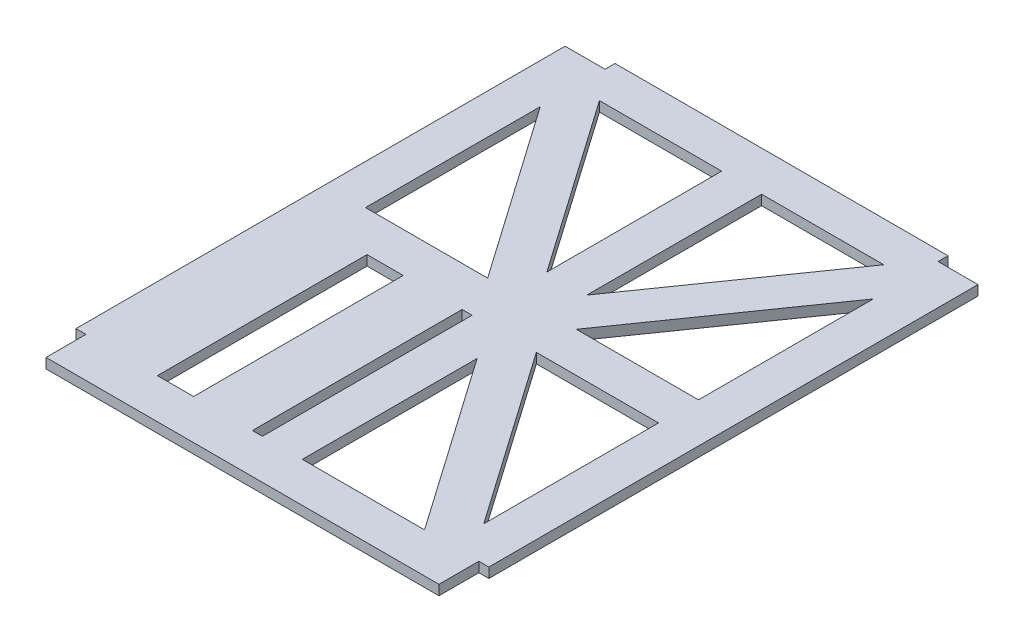
SolidWorks part; units mm, degrees
ref_plane "Front Plane" through (0, 0, 0) normal (0, 0, 1) x (1, 0, 0)
ref_plane "Top Plane" through (0, 0, 0) normal (0, 1, 0) x (1, 0, 0)
ref_plane "Right Plane" through (0, 0, 0) normal (1, 0, 0) x (0, 0, -1)
sketch "Sketch1" plane through (0, 0, 0) normal (0, 1, 0) x (1, 0, 0)
  line L0 (0, -85.5686) -> (0, 85.8814) construction
  line L1 (-52.96, 85.8814) -> (52.96, 85.8814)
  line L2 (-65.66, 82.7064) -> (-65.66, -72.8686)
  line L3 (-62.485, -85.5686) -> (62.485, -85.5686)
  line L4 (65.66, 82.7064) -> (65.66, -72.8686)
  line L5 (-65.66, 0.1564) -> (65.66, 0.1564) construction
  line L6 (-52.96, 6.5064) -> (-14.0978, 6.5064)
  line L7 (-45.2122, 73.1814) -> (-6.35, 73.1814)
  line L8 (-52.96, 62.0984) -> (-52.96, 6.5064)
  line L9 (-39.7545, -72.8686) -> (-28.2545, -72.8686)
  line L10 (52.96, 62.0984) -> (52.96, 6.5064)
  line L11 (-6.35, 73.1814) -> (-6.35, 17.5895)
  line L12 (6.35, 73.1814) -> (6.35, 17.5895)
  line L13 (14.0978, -6.1936) -> (52.96, -6.1936)
  line L14 (-52.96, 73.1814) -> (-6.35, 6.5064) construction
  line L15 (52.96, 73.1814) -> (6.35, 6.5064) construction
  line L16 (6.35, -6.1936) -> (52.96, -72.8686) construction
  line L17 (-52.96, 62.0984) -> (-14.0978, 6.5064)
  line L18 (-45.2122, 73.1814) -> (-6.35, 17.5895)
  line L19 (45.2122, 73.1814) -> (6.35, 17.5895)
  line L20 (52.96, 62.0984) -> (14.0978, 6.5064)
  line L21 (6.35, -17.2766) -> (45.2122, -72.8686)
  line L22 (14.0978, -6.1936) -> (52.96, -61.7855)
  line L23 (-34.0045, -6.1936) -> (-34.0045, -72.8686) construction
  line L24 (-39.7545, -6.1936) -> (-28.2545, -6.1936)
  line L25 (-39.7545, -6.1936) -> (-39.7545, -72.8686)
  line L27 (-28.2545, -6.1936) -> (-28.2545, -72.8686)
  line L28 (-65.66, 82.7064) -> (-52.96, 82.7064)
  line L29 (-52.96, 82.7064) -> (-52.96, 85.8814)
  line L30 (65.66, 82.7064) -> (52.96, 82.7064)
  line L31 (52.96, 82.7064) -> (52.96, 85.8814)
  line L32 (-65.66, -72.8686) -> (-62.485, -72.8686)
  line L33 (-62.485, -72.8686) -> (-62.485, -85.5686)
  line L34 (65.66, -72.8686) -> (62.485, -72.8686)
  line L35 (62.485, -72.8686) -> (62.485, -85.5686)
  line L36 (6.35, 73.1814) -> (45.2122, 73.1814)
  line L37 (-9.525, -6.1936) -> (-6.35, -6.1936)
  line L38 (-9.525, -6.1936) -> (-9.525, -72.8686)
  line L39 (-9.525, -72.8686) -> (-6.35, -72.8686)
  line L40 (-6.35, -6.1936) -> (-6.35, -72.8686)
  line L41 (14.0978, 6.5064) -> (52.96, 6.5064)
  line L42 (6.35, -17.2766) -> (6.35, -72.8686)
  line L43 (52.96, -6.1936) -> (52.96, -61.7855)
  line L45 (6.35, -72.8686) -> (45.2122, -72.8686)
  point P36 (-34.0045, -32.2513)
  dimension "D3" = 12.7
  dimension "D4" = 12.7
  dimension "D5" = 12.7
  dimension "D6" = 12.7
  dimension "D7" = 6.35
  dimension "D8" = 6.35
  dimension "D9" = 6.35
  dimension "D10" = 6.35
  dimension "D11" = 6.35
  dimension "D12" = 6.35
  dimension "D13" = 6.35
  dimension "D14" = 6.35
  dimension "D15" = 6.35
  dimension "D16" = 6.35
  dimension "D17" = 27.6545
  dimension "D18" = 11.5
  dimension "D19" = 12.7
  dimension "D20" = 12.7
  dimension "D21" = 3.175
  dimension "D22" = 12.7
  dimension "D23" = 12.7
  dimension "D24" = 12.7
  dimension "D25" = 3.175
  dimension "D26" = 3.175
  dimension "D27" = 3.175
  dimension "D28" = 12.7
  dimension "D29" = 6.35
extrude "Boss-Extrude1" add sketch "Sketch1" along normal blind 3.175
